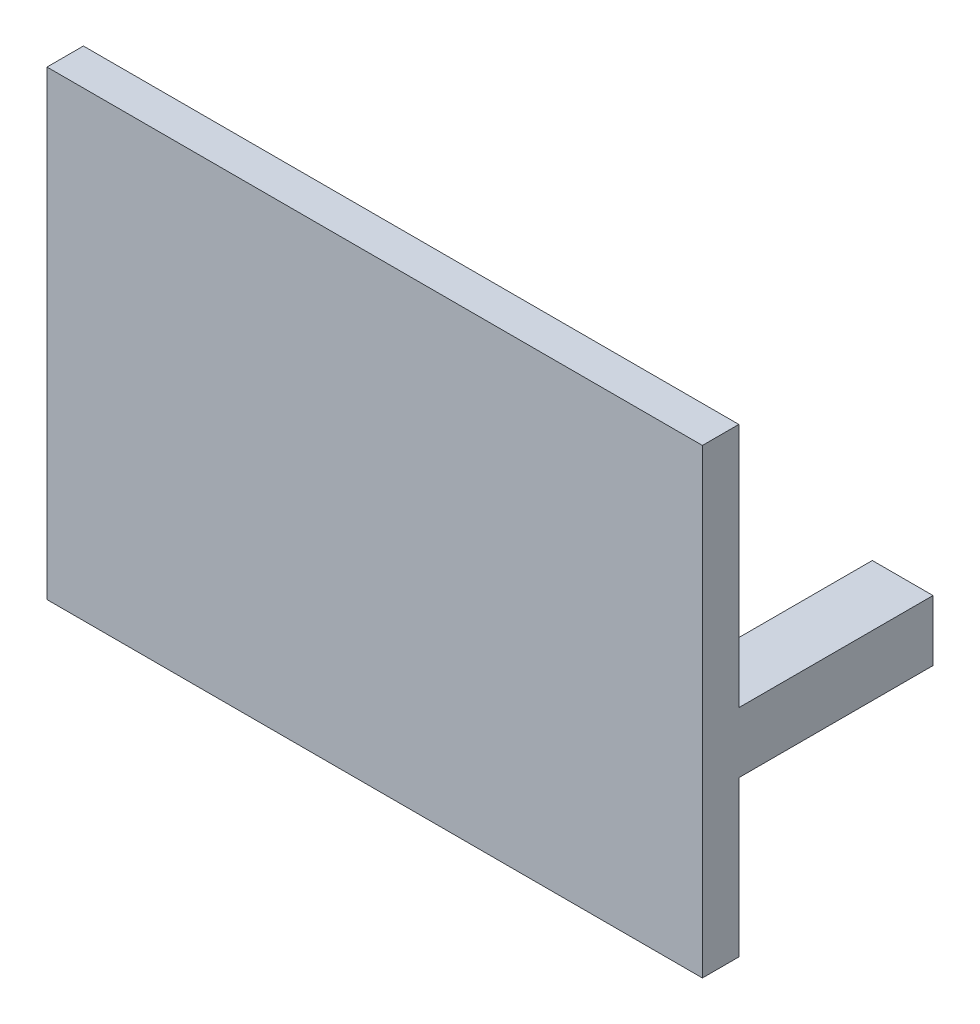
SolidWorks part; units mm, degrees
ref_plane "Front Plane" through (0, 0, 0) normal (0, 0, 1) x (1, 0, 0)
ref_plane "Top Plane" through (0, 0, 0) normal (0, 1, 0) x (1, 0, 0)
ref_plane "Right Plane" through (0, 0, 0) normal (1, 0, 0) x (0, 0, -1)
sketch "Sketch1" plane through (0, 0, 0) normal (0, 0, 1) x (1, 0, 0)
  line L1 (0, 0) -> (54, 0)
  line L2 (0, 0) -> (0, 38)
  line L3 (0, 38) -> (54, 38)
  line L4 (54, 0) -> (54, 38)
  line L5 (27, 38) -> (27, 0) construction
  line L6 (0, 19) -> (54, 19) construction
  point P160 (27, 19)
  dimension "D1" = 38
  dimension "D2" = 54
extrude "Boss-Extrude1" add sketch "Sketch1" along normal blind 3
sketch "Sketch2" plane through (0, 0, 0) normal (0, 0, 1) x (1, 0, 0)
  line L0 (0, 0) -> (54, 0) construction
  line L1 (0, 38) -> (0, 0) construction
  line L2 (54, 0) -> (54, 38) construction
  line L3 (54, 38) -> (0, 38) construction
  line L5 (10.4, 10.2) -> (15.4, 10.2)
  line L6 (10.4, 10.2) -> (10.4, 5.2)
  line L7 (10.4, 5.2) -> (15.4, 5.2)
  line L8 (15.4, 10.2) -> (15.4, 5.2)
  line L9 (12.9, 5.2) -> (12.9, 10.2) construction
  line L10 (10.4, 7.7) -> (15.4, 7.7) construction
  line L11 (49, 17.79) -> (54, 17.79)
  line L12 (49, 17.79) -> (49, 12.79)
  line L13 (49, 12.79) -> (54, 12.79)
  line L14 (54, 17.79) -> (54, 12.79)
  line L15 (51.5, 12.79) -> (51.5, 17.79) construction
  line L16 (49, 15.29) -> (54, 15.29) construction
  circle A0 centre (12.9, 7.7) radius 1.6
  circle A1 centre (51.5, 15.29) radius 1.6
  dimension "D3" = 3.2
  dimension "D4" = 3.2
  dimension "D1" = 7.7
  dimension "D2" = 12.9
  dimension "D5" = 2.5
  dimension "D6" = 22.71
  dimension "D7" = 5
  dimension "D8" = 5
  dimension "D9" = 5
extrude "Boss-Extrude2" add sketch "Sketch2" against normal blind 16
